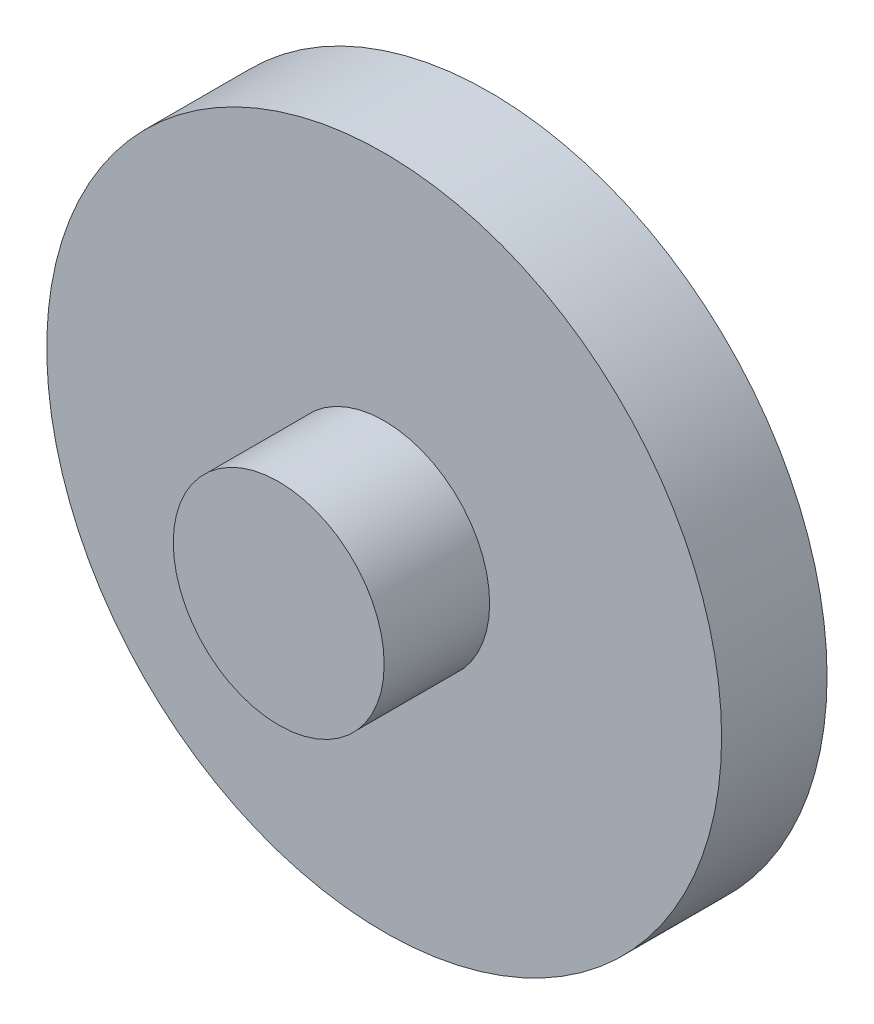
SolidWorks part; units mm, degrees
ref_plane "前视基准面" through (0, 0, 0) normal (0, 0, 1) x (1, 0, 0)
ref_plane "上视基准面" through (0, 0, 0) normal (0, 1, 0) x (1, 0, 0)
ref_plane "右视基准面" through (0, 0, 0) normal (1, 0, 0) x (0, 0, -1)
sketch "草图1" plane through (0, 0, 0) normal (0, 0, 1) x (1, 0, 0)
  circle A0 centre (0, 0) radius 32
extrude "凸台-拉伸1" add sketch "草图1" along normal blind 10
sketch "草图2" plane through (0, 0, 10) normal (0, 0, 1) x (1, 0, 0)
  circle A0 centre (0, 0) radius 10
extrude "凸台-拉伸2" add sketch "草图2" along normal blind 10
